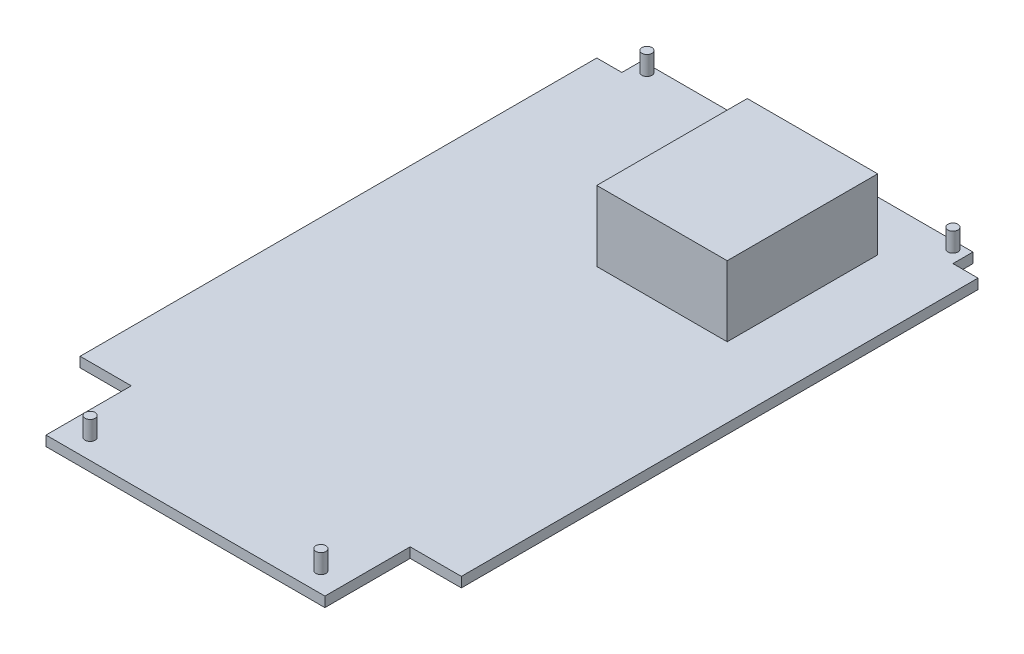
SolidWorks part; units mm, degrees
ref_plane "Front Plane" through (0, 0, 0) normal (0, 0, 1) x (1, 0, 0)
ref_plane "Top Plane" through (0, 0, 0) normal (0, 1, 0) x (1, 0, 0)
ref_plane "Right Plane" through (0, 0, 0) normal (1, 0, 0) x (0, 0, -1)
sketch "Sketch1" plane through (0, 0, 0) normal (0, 1, 0) x (1, 0, 0)
  line L0 (0, 0) -> (66, 0)
  line L1 (0, 0) -> (0, -4)
  line L2 (66, 0) -> (66, -4)
  line L3 (0, -4) -> (-5, -4)
  line L4 (66, -4) -> (71, -4)
  line L5 (-5, -4) -> (-5, -107)
  line L6 (71, -4) -> (71, -107)
  line L7 (-5, -107) -> (5.2, -107)
  line L8 (71, -107) -> (60.8, -107)
  line L9 (5.2, -107) -> (5.2, -115)
  line L10 (60.8, -107) -> (60.8, -115)
  line L11 (5.2, -115) -> (5.2, -124)
  line L12 (60.8, -115) -> (60.8, -124)
  line L13 (5.2, -124) -> (60.8, -124)
  dimension "D1" = 66
  dimension "D2" = 4
  dimension "D3" = 4
  dimension "D4" = 5
  dimension "D5" = 5
  dimension "D6" = 103
  dimension "D7" = 103
  dimension "D8" = 10.2
  dimension "D9" = 10.2
  dimension "D10" = 8
  dimension "D11" = 8
  dimension "D12" = 9
  dimension "D13" = 9
extrude "Boss-Extrude1" add sketch "Sketch1" along normal blind 2
sketch "Sketch2" plane through (0, 2, 0) normal (0, 1, 0) x (1, 0, 0)
  line L0 (5.2, -107) -> (5.2, -124) construction
  line L1 (5.2, -124) -> (60.8, -124) construction
  line L2 (60.8, -124) -> (60.8, -107) construction
  line L3 (0, 0) -> (0, -4) construction
  line L4 (66, 0) -> (0, 0) construction
  line L5 (66, -4) -> (66, 0) construction
  circle A0 centre (10, -120) radius 1
  circle A1 centre (56, -120) radius 1
  circle A2 centre (2.5, -1.5) radius 1
  circle A3 centre (63.5, -1.5) radius 1
  point P22 (63.378, -1.3839)
  dimension "D3" = 2
  dimension "D4" = 2
  dimension "D8" = 2
  dimension "D10" = 2
  dimension "D1" = 4.8
  dimension "D2" = 4
  dimension "D5" = 4.8
  dimension "D6" = 4
  dimension "D7" = 2.5
  dimension "D9" = 1.5
  dimension "D11" = 2.5
  dimension "D12" = 1.5
extrude "Boss-Extrude2" add sketch "Sketch2" along normal blind 3.8
sketch "Sketch3" plane through (0, 0, 0) normal (0, -1, 0) x (-1, 0, 0)
  line L0 (5, -4) -> (5, -107) construction
  line L1 (-57, -10) -> (-31, -10)
  line L2 (-57, -10) -> (-57, -40)
  line L3 (-57, -40) -> (-31, -40)
  line L4 (-31, -10) -> (-31, -40)
  line L6 (-71, -107) -> (-71, -4) construction
  line L7 (-66, 0) -> (0, 0) construction
  dimension "D1" = 14
  dimension "D2" = 30
  dimension "D3" = 36
  dimension "D4" = 10
extrude "Boss-Extrude3" add sketch "Sketch3" against normal blind 16
sketch "Sketch4" plane through (0, 16, 0) normal (0, 1, 0) x (1, 0, 0)
  line L0 (31, -10) -> (57, -10) construction
  line L1 (32, -39) -> (56, -39)
  line L2 (32, -39) -> (32, -11)
  line L3 (32, -11) -> (56, -11)
  line L4 (56, -39) -> (56, -11)
  line L5 (57, -10) -> (57, -40) construction
  dimension "D1" = 1
  dimension "D2" = 1
  dimension "D3" = 1
  dimension "D4" = 1
extrude "Cut-Extrude1" cut sketch "Sketch4" against normal blind 26
sketch "Sketch5" plane through (32, 0, 0) normal (1, 0, 0) x (0, 0, -1)
  line L0 (-11, 0) -> (-11, 16) construction
  line L1 (-11, 16) -> (-39, 16)
  line L2 (-11, 16) -> (-11, 2)
  line L3 (-11, 2) -> (-39, 2)
  line L4 (-39, 16) -> (-39, 2)
  line L5 (-39, 0) -> (-39, 16) construction
  dimension "D1" = 2
  dimension "D2" = 0
  dimension "D3" = 0
  dimension "D4" = 0
extrude "Cut-Extrude2" cut sketch "Sketch5" against normal up to surface (1 mm away) up to face at (31, 9, 25)
sketch "Sketch6" plane through (56, 0, 0) normal (-1, 0, 0) x (0, 0, 1)
  line L0 (39, 16) -> (11, 16) construction
  line L1 (11, 16) -> (39, 16)
  line L2 (11, 16) -> (11, 15)
  line L3 (11, 15) -> (39, 15)
  line L4 (39, 16) -> (39, 15)
  line L5 (39, 0) -> (39, 16) construction
  dimension "D1" = 0
  dimension "D2" = 0
  dimension "D3" = 1
  dimension "D4" = 0
extrude "Boss-Extrude4" add sketch "Sketch6" along normal blind 25
